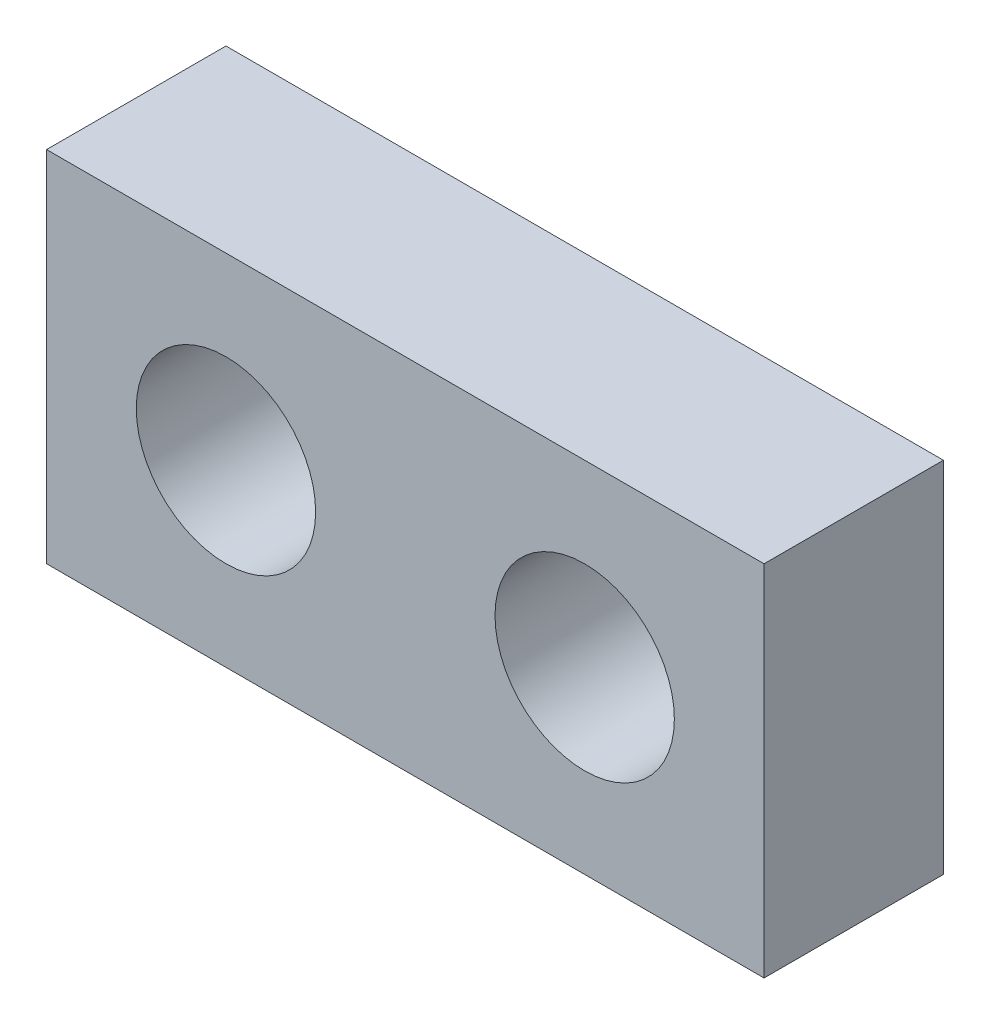
SolidWorks part; units mm, degrees
ref_plane "前视基准面" through (0, 0, 0) normal (0, 0, 1) x (1, 0, 0)
ref_plane "上视基准面" through (0, 0, 0) normal (0, 1, 0) x (1, 0, 0)
ref_plane "右视基准面" through (0, 0, 0) normal (1, 0, 0) x (0, 0, -1)
sketch "草图1" plane through (0, 0, 0) normal (0, 0, 1) x (1, 0, 0)
  line L1 (10, -5) -> (-10, -5)
  line L2 (10, -5) -> (10, 5)
  line L3 (10, 5) -> (-10, 5)
  line L4 (-10, -5) -> (-10, 5)
  line L5 (10, -5) -> (-10, 5) construction
  line L6 (10, 5) -> (-10, -5) construction
  circle A0 centre (-5, 0) radius 2.5
  circle A1 centre (5, 0) radius 2.5
  point P0 (0, 0)
  point P10 (0, 0)
  dimension "D3" = 5
  dimension "D4" = 5
  dimension "D1" = 10
  dimension "D2" = 20
  dimension "D5" = 10
  dimension "D6" = 5
extrude "凸台-拉伸1" add sketch "草图1" along normal blind 5
